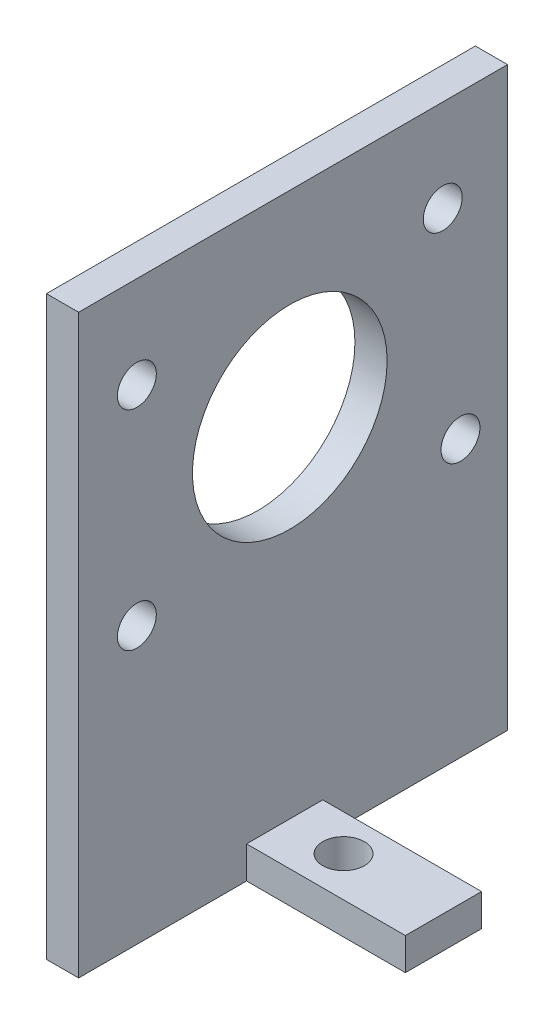
SolidWorks part; units mm, degrees
ref_plane "Front Plane" through (0, 0, 0) normal (0, 0, 1) x (1, 0, 0)
ref_plane "Top Plane" through (0, 0, 0) normal (0, 1, 0) x (1, 0, 0)
ref_plane "Right Plane" through (0, 0, 0) normal (1, 0, 0) x (0, 0, -1)
sketch "Sketch1" plane through (0, 0, 0) normal (0, 0, 1) x (1, 0, 0)
  line L0 (0, 0) -> (0, 39.1564)
  line L1 (0, 0) -> (16.4406, 0)
  dimension "D1" = 39.1564
  dimension "D2" = 16.4406
extrude "Extrude-Thin2" add sketch "Sketch1" against normal blind 30.852 thin thin type one direction wall 2.3152
sketch "Sketch2" plane through (0, 0, 0) normal (0, 1, 0) x (1, 0, 0)
  circle A0 centre (4.0977, 14.9571) radius 1.5
  dimension "D1" = 3
extrude "Cut-Extrude1" cut sketch "Sketch2" against normal through all
sketch "Sketch4" plane through (0, 0, 0) normal (1, 0, 0) x (0, 0, -1)
  circle A0 centre (15.189, 25.0395) radius 7
  dimension "D1" = 14
extrude "Cut-Extrude3" cut sketch "Sketch4" against normal through all
sketch "Sketch6" plane through (0, 0, 0) normal (1, 0, 0) x (0, 0, -1)
  line L0 (30.852, 0) -> (0, 0) construction
  circle A0 centre (4.189, 32.5395) radius 1.4
  circle A1 centre (4.189, 17.5395) radius 1.4
  circle A2 centre (26.189, 32.5395) radius 1.4
  circle A3 centre (27.4649, 17.5395) radius 1.4
  circle A4 centre (15.189, 25.0395) radius 7 construction
  point P8 (0, 0)
  dimension "D1" = 2.8
  dimension "D2" = 2.8
  dimension "D3" = 2.8
  dimension "D4" = 2.8
  dimension "D9" = 11
  dimension "D10" = 7.5
  dimension "D5" = 15
  dimension "D6" = 15
  dimension "D7" = 22
  dimension "D8" = 11
  dimension "D11" = 7.5
  dimension "D12" = 17.5395
extrude "Cut-Extrude5" cut sketch "Sketch6" against normal through all
sketch "Sketch7" plane through (0, 0, 0) normal (0, 1, 0) x (1, 0, 0)
  line L0 (0, 30.852) -> (0, 0) construction
  line L1 (0, 12.0812) -> (16.4406, 12.0812)
  line L2 (0, 12.0812) -> (0, 0)
  line L3 (0, 0) -> (16.4406, 0)
  line L4 (16.4406, 12.0812) -> (16.4406, 0)
  line L5 (16.4406, 30.852) -> (16.4406, 0) construction
  line L6 (0, 30.852) -> (16.4406, 30.852)
  line L7 (0, 30.852) -> (0, 17.5614)
  line L8 (0, 17.5614) -> (16.4406, 17.5614)
  line L9 (16.4406, 30.852) -> (16.4406, 17.5614)
  line L10 (0, 30.852) -> (0, 0) construction
  point P14 (0, 0)
  point P15 (0, 12.0812)
  point P18 (0, 17.5614)
extrude "Cut-Extrude6" cut sketch "Sketch7" against normal through all
sketch "Sketch8" plane through (0, 0, 0) normal (0, 1, 0) x (1, 0, 0)
  line L0 (0, 17.5614) -> (16.4406, 17.5614) construction
  line L1 (11.4209, 17.5614) -> (16.4406, 17.5614)
  line L2 (11.4209, 17.5614) -> (11.4209, 12.0812)
  line L3 (11.4209, 12.0812) -> (16.4406, 12.0812)
  line L4 (16.4406, 17.5614) -> (16.4406, 12.0812)
  line L5 (16.4406, 12.0812) -> (0, 12.0812) construction
extrude "Cut-Extrude7" cut sketch "Sketch8" against normal through all
